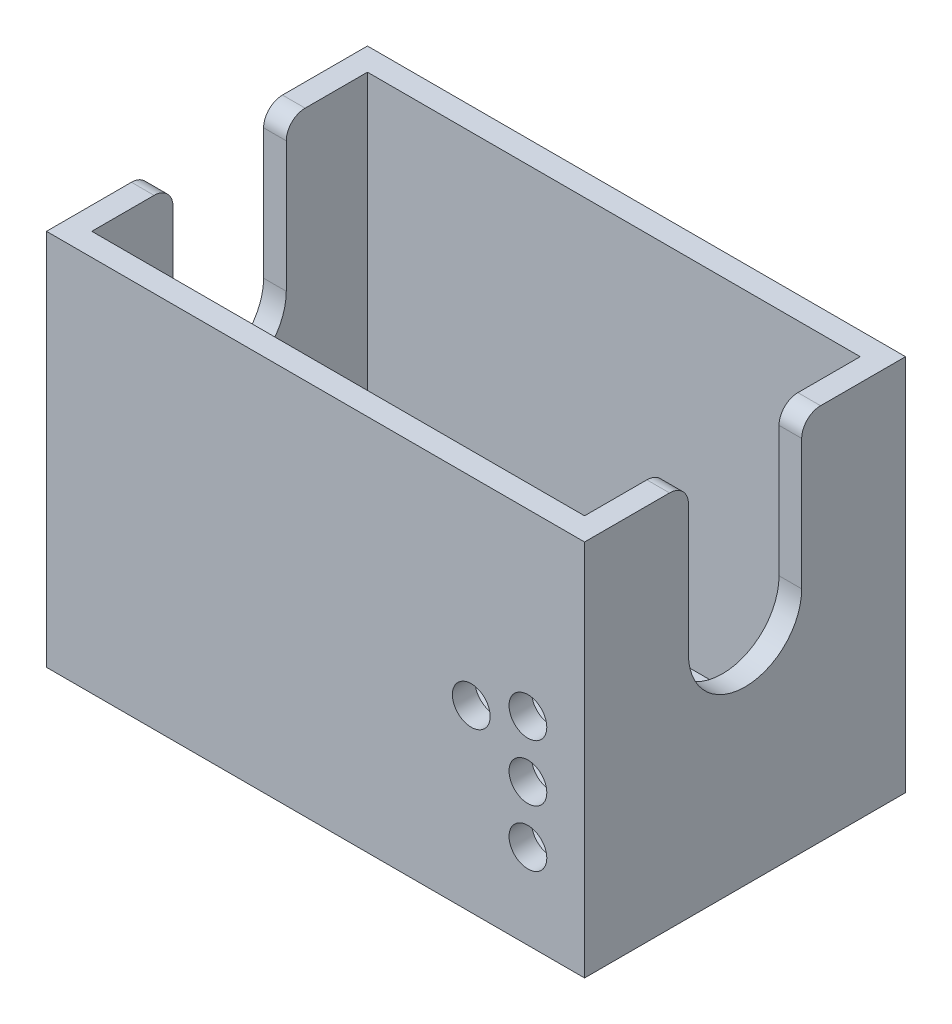
SolidWorks part; units mm, degrees
ref_plane "Front Plane" through (0, 0, 0) normal (0, 0, 1) x (1, 0, 0)
ref_plane "Top Plane" through (0, 0, 0) normal (0, 1, 0) x (1, 0, 0)
ref_plane "Right Plane" through (0, 0, 0) normal (1, 0, 0) x (0, 0, -1)
sketch "Sketch1" plane through (0, 0, 0) normal (0, 1, 0) x (1, 0, 0)
  line L1 (142.5, 85) -> (-142.5, 85)
  line L2 (142.5, 85) -> (142.5, -85)
  line L3 (142.5, -85) -> (-142.5, -85)
  line L4 (-142.5, 85) -> (-142.5, -85)
  line L5 (142.5, 85) -> (-142.5, -85) construction
  line L6 (142.5, -85) -> (-142.5, 85) construction
  point P0 (0, 0)
  point P6 (142.5, 0)
  point P7 (-142.5, 0)
  dimension "D1" = 285
  dimension "D2" = 170
extrude "Boss-Extrude1" add sketch "Sketch1" along normal blind 200
shell "Shell1" thickness 12
sketch "Sketch2" plane through (142.5, 0, 0) normal (1, 0, 0) x (0, 0, -1)
  line L0 (0, 0) -> (0, 200) construction
  line L1 (-85, 200) -> (85, 200) construction
  line L2 (-85, 121) -> (85, 121) construction
  line L3 (-85, 200) -> (-85, 0) construction
  line L4 (85, 200) -> (85, 0) construction
  line L5 (-85, 200) -> (-40, 200)
  line L6 (-30, 121) -> (-30, 190)
  line L7 (30, 121) -> (30, 190)
  line L8 (40, 200) -> (85, 200)
  arc A0 (-30, 121) -> (30, 121) centre (0, 121) ccw
  arc A1 (30, 190) -> (40, 200) centre (40, 190) cw
  arc A2 (-30, 190) -> (-40, 200) centre (-40, 190) ccw
  point P21 (30, 200)
  point P24 (-30, 200)
  line M7 (85, 200) -> (-85, 200)
  dimension "D2" = 60
  dimension "D3" = 10
  dimension "D1" = 79
extrude "Cut-Extrude1" cut sketch "Sketch2" against normal through all and the other way through all contours A2 L6 A0 L7 A1 M7
sketch "Sketch3" plane through (0, 0, 85) normal (0, 0, 1) x (1, 0, 0)
  line L0 (-60.0364, 200) -> (-60.0364, 0) construction
  line L1 (-142.5, 200) -> (142.5, 200) construction
  line L2 (-142.5, 0) -> (142.5, 0) construction
  line L3 (-60.0364, 0) -> (-72.6022, 0) construction
  line L4 (-72.6022, 0) -> (-72.6022, 200) construction
  line L5 (-72.6022, 200) -> (-60.0364, 200) construction
  line L6 (0, 0) -> (0, 200) construction
  line L7 (50.7285, 200) -> (50.7285, 0) construction
  line L8 (50.7285, 0) -> (64.6904, 0) construction
  line L9 (64.6904, 0) -> (64.6904, 200) construction
  line L10 (64.6904, 200) -> (50.7285, 200) construction
  line L11 (-72.6022, 162.9604) -> (64.6904, 162.9604) construction
  line L12 (64.6904, 162.9604) -> (-72.6022, 75) construction
  line L13 (-72.6022, 75) -> (64.6904, 75) construction
  line L14 (-72.6022, 175) -> (64.6904, 175) construction
  line L15 (13.9647, 175) -> (13.9647, 75) construction
  line L16 (13.9647, 125) -> (179.8354, 125) construction
  dimension "D1" = 100
  dimension "D2" = 75
  dimension "D3" = 137.2926
sketch "Sketch4" plane through (0, 0, 85) normal (0, 0, 1) x (1, 0, 0)
  line L0 (130.5, 200) -> (130.5, 0) construction
  line L1 (-142.5, 200) -> (142.5, 200) construction
  line L2 (-142.5, 0) -> (142.5, 0) construction
  line L3 (142.5, 200) -> (142.5, 0) construction
  circle A0 centre (112.5, 105) radius 10
  circle A1 centre (112.5, 75) radius 10
  circle A2 centre (112.5, 45) radius 10
  circle A3 centre (82.5, 95) radius 10
  point P14 (0, 0)
  dimension "D2" = 20
  dimension "D3" = 95
  dimension "D7" = 20
  dimension "D1" = 12
  dimension "D4" = 30
  dimension "D5" = 30
  dimension "D6" = 30
  dimension "D8" = 105
  dimension "D9" = 60
extrude "Cut-Extrude2" cut sketch "Sketch4" against normal up to surface (12 mm away) up to face at (0, 106, 73)
